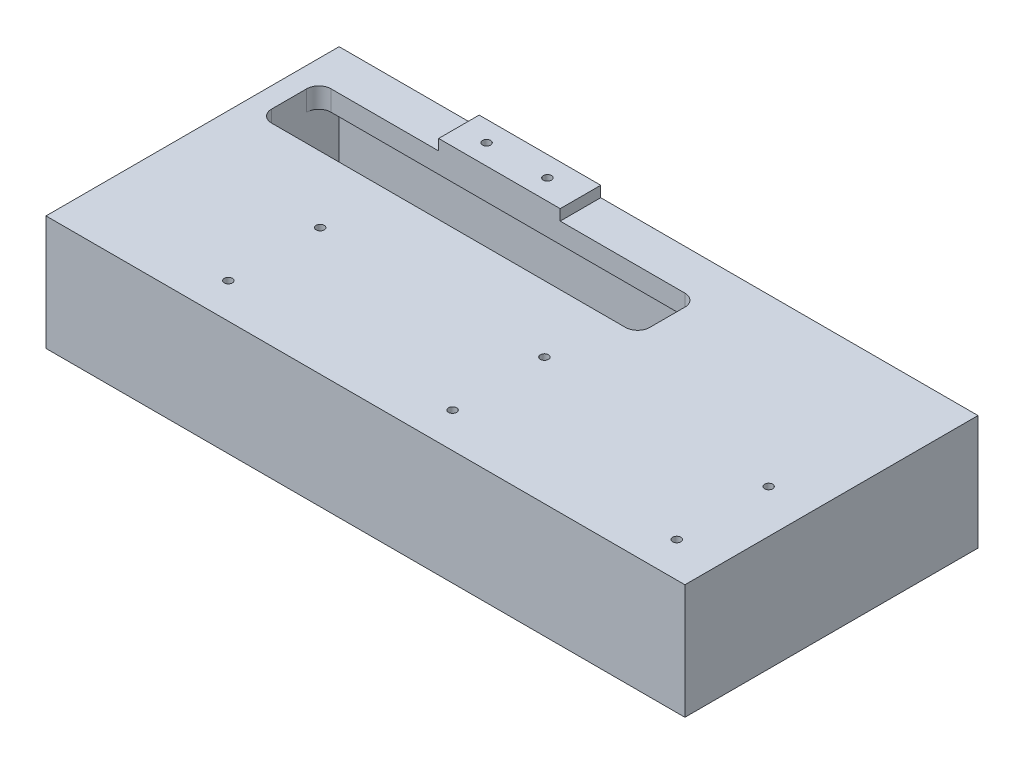
SolidWorks part; units mm, degrees
ref_plane "Front Plane" through (0, 0, 0) normal (0, 0, 1) x (1, 0, 0)
ref_plane "Top Plane" through (0, 0, 0) normal (0, 1, 0) x (1, 0, 0)
ref_plane "Right Plane" through (0, 0, 0) normal (1, 0, 0) x (0, 0, -1)
sketch "Sketch1" plane through (0, 0, 0) normal (0, 1, 0) x (1, 0, 0)
  line L1 (236.5, -108.5) -> (-236.5, -108.5)
  line L2 (236.5, -108.5) -> (236.5, 108.5)
  line L3 (236.5, 108.5) -> (-236.5, 108.5)
  line L4 (-236.5, -108.5) -> (-236.5, 108.5)
  line L5 (236.5, -108.5) -> (-236.5, 108.5) construction
  line L6 (236.5, 108.5) -> (-236.5, -108.5) construction
  point P0 (0, 0)
  dimension "D1" = 473
  dimension "D2" = 217
extrude "Boss-Extrude1" add sketch "Sketch1" along normal blind 85
sketch "Sketch2" plane through (0, 85, 0) normal (0, 1, 0) x (1, 0, 0)
  line L0 (-236.5, -108.5) -> (236.5, -108.5) construction
  line L1 (-221.5, 78.5) -> (58.5, 78.5)
  line L2 (-221.5, 78.5) -> (-221.5, 34.5)
  line L3 (-221.5, 34.5) -> (58.5, 34.5)
  line L4 (58.5, 78.5) -> (58.5, 34.5)
  line L5 (-236.5, 108.5) -> (-236.5, -108.5) construction
  dimension "D1" = 44
  dimension "D2" = 143
  dimension "D3" = 15
  dimension "D4" = 280
extrude "Cut-Extrude1" cut sketch "Sketch2" against normal blind 15
sketch "Sketch3" plane through (0, 0, 0) normal (0, -1, 0) x (1, 0, 0)
  line L8 (-221.5, 93.5) -> (-221.5, -93.5)
  line L9 (-221.5, -93.5) -> (221.5, -93.5)
  line L10 (221.5, -93.5) -> (221.5, 93.5)
  line L11 (221.5, 93.5) -> (-221.5, 93.5)
  line L12 (-221.5, 93.5) -> (-221.5, -93.5)
  line L13 (-221.5, -93.5) -> (221.5, -93.5)
  line L14 (221.5, -93.5) -> (221.5, 93.5)
  line L15 (221.5, 93.5) -> (-221.5, 93.5)
  dimension "D1" = 15
extrude "Cut-Extrude2" cut sketch "Sketch3" against normal blind 70
fillet "Fillet1" radius 9 4 edges at (-221.5, 77.5, -34.5) (58.5, 77.5, -34.5) (58.5, 77.5, -78.5) (-221.5, 77.5, -78.5)
sketch "Sketch4" plane through (0, 85, 0) normal (0, 1, 0) x (1, 0, 0)
  line L0 (236.5, 108.5) -> (-236.5, 108.5) construction
  line L1 (-132.81, 108.5) -> (-42.81, 108.5)
  line L2 (-132.81, 108.5) -> (-132.81, 78.5)
  line L3 (-132.81, 78.5) -> (-42.81, 78.5)
  line L4 (-42.81, 108.5) -> (-42.81, 78.5)
  line L5 (49.5, 78.5) -> (-212.5, 78.5) construction
  line L6 (-236.5, 108.5) -> (-236.5, -108.5) construction
  dimension "D1" = 103.69
  dimension "D2" = 90
extrude "Boss-Extrude2" add sketch "Sketch4" along normal blind 8
sketch "Sketch5" plane through (0, 93, 0) normal (0, 1, 0) x (1, 0, 0)
  line L0 (-132.81, 78.5) -> (-42.81, 78.5) construction
  line L1 (-42.81, 108.5) -> (-132.81, 108.5) construction
  line L2 (-42.81, 78.5) -> (-42.81, 108.5) construction
  circle A0 centre (-112.31, 93.5) radius 3
  circle A1 centre (-67.31, 93.5) radius 3
  dimension "D4" = 6
  dimension "D6" = 6
  dimension "D1" = 15
  dimension "D2" = 15
  dimension "D3" = 24.5
  dimension "D5" = 45
extrude "Cut-Extrude3" cut sketch "Sketch5" against normal blind 15
sketch "Sketch6" plane through (0, 85, 0) normal (0, 1, 0) x (1, 0, 0)
  line L0 (236.5, -108.5) -> (236.5, 108.5) construction
  line L1 (-236.5, -108.5) -> (236.5, -108.5) construction
  circle A0 centre (-127.5, -82.5) radius 3
  circle A1 centre (-127.5, -14.5) radius 3
  circle A2 centre (38.5, -14.5) radius 3
  circle A3 centre (204.5, -14.5) radius 3
  circle A4 centre (204.5, -82.5) radius 3
  circle A5 centre (38.5, -82.5) radius 3
  dimension "D1" = 6
  dimension "D2" = 32
  dimension "D3" = 166
  dimension "D4" = 166
  dimension "D5" = 26
  dimension "D6" = 68
extrude "Cut-Extrude4" cut sketch "Sketch6" against normal blind 15
